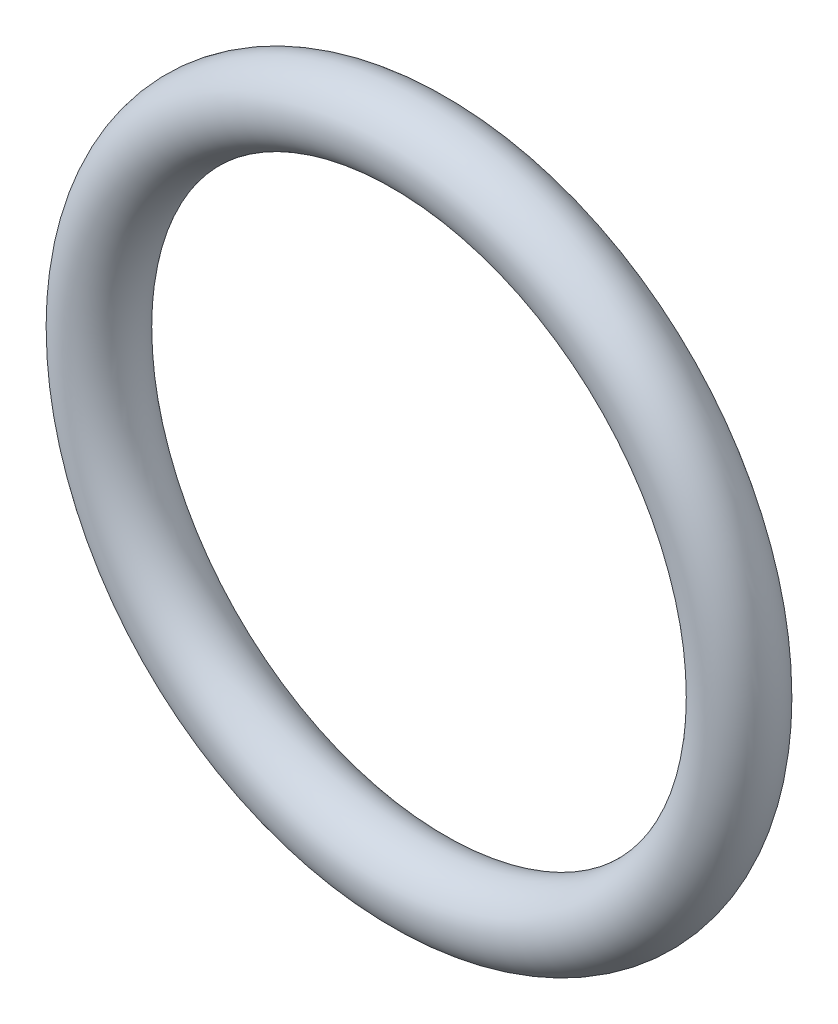
SolidWorks part; units mm, degrees
material "Rubber"
ref_plane "Plano frontal" through (0, 0, 0) normal (0, 0, 1) x (1, 0, 0)
ref_plane "Plano superior" through (0, 0, 0) normal (0, 1, 0) x (1, 0, 0)
ref_plane "Plano direito" through (0, 0, 0) normal (1, 0, 0) x (0, 0, -1)
sketch "Esboço1" plane through (0, 0, 0) normal (0, 0, 1) x (1, 0, 0)
  circle A0 centre (0, 0) radius 12.5 construction
  circle A1 centre (0, 0) radius 10.711
  dimension "D1" = 25
sketch "Esboço3" plane through (0, 0, 0) normal (0, 0, 1) x (1, 0, 0)
  line L0 (10.711, 0) -> (10.711, 4.4645) construction
  circle A0 centre (0, 0) radius 10.711 construction
sketch "Esboço6" plane through (0, 0, 0) normal (0, 1, 0) x (1, 0, 0)
  line L0 (0, 2.0437) -> (0, 0) construction
  circle A0 centre (10.711, 0) radius 1.25
  dimension "D1" = 2.5
revolve "Revolução1" add sketch "Esboço6" angle 360 about L0
ref_plane "Plano1" through (0, 0, 1.25) normal (0, 0, 1) x (1, 0, 0)
sketch "Esboço7" plane through (0, 0, 1.25) normal (0, 0, 1) x (1, 0, 0)
  circle A0 centre (0, 0) radius 2.8691
surface "Superfície-Extrusão1" sketch "Esboço7" parameters "D1"=2
